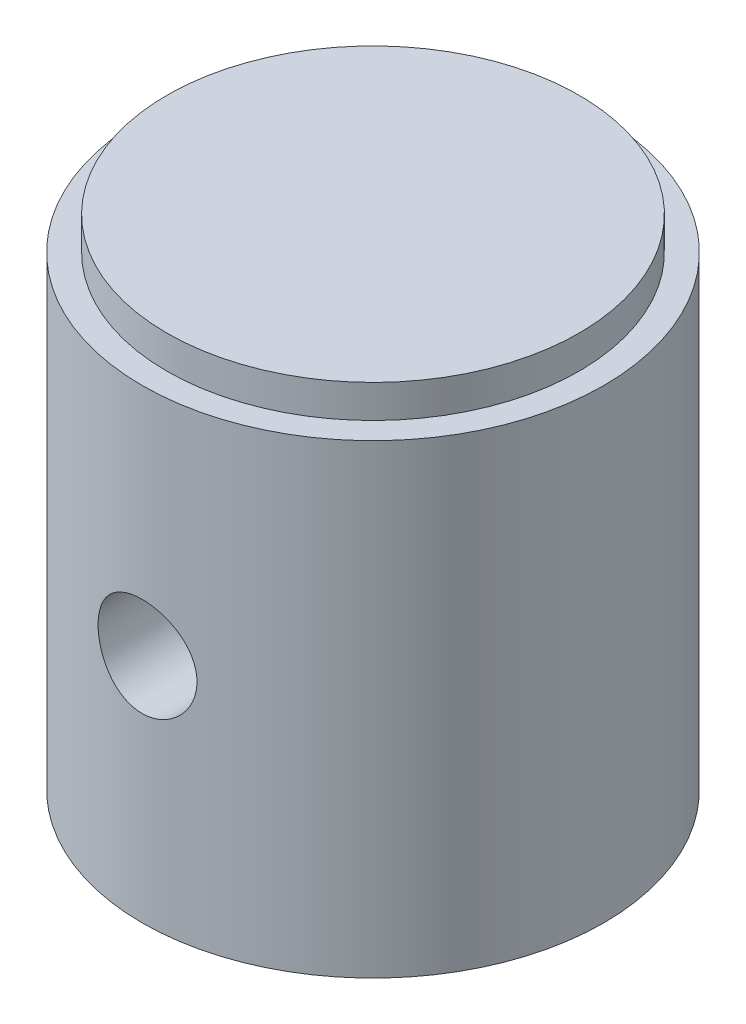
SolidWorks part; units mm, degrees
ref_plane "Front Plane" through (0, 0, 0) normal (0, 0, 1) x (1, 0, 0)
ref_plane "Top Plane" through (0, 0, 0) normal (0, 1, 0) x (1, 0, 0)
ref_plane "Right Plane" through (0, 0, 0) normal (1, 0, 0) x (0, 0, -1)
sketch "Sketch1" plane through (0, 0, 0) normal (0, 0, 1) x (1, 0, 0)
  line L0 (0, -49.5119) -> (0, 49.5119) construction
  line L1 (0, 27.1024) -> (-6.25, 27.1024)
  line L2 (-6.25, 27.1024) -> (-6.25, 26.1024)
  line L3 (-6.25, 26.1024) -> (-7, 26.1024)
  line L4 (-7, 26.1024) -> (-7, 11.9867)
  line L5 (-5.1038, 11.9867) -> (-7, 11.9867)
  line L6 (0, 27.1024) -> (0, 25.6024)
  line L7 (0, 25.6024) -> (-4.3916, 22.9636)
  line L8 (-4.3916, 22.9636) -> (-4.3916, 15.9636)
  line L9 (-5.1038, 11.9867) -> (0, 11.9867)
  line L12 (-4.3916, 18.9636) -> (-4.3916, 15.9636)
  line L13 (-4.3916, 15.9636) -> (-5.1121, 13.9843)
  line L14 (-5.1121, 13.9843) -> (-5.8391, 11.9867)
  line L15 (-4.3916, 22.9636) -> (-4.3916, 18.9636)
  point P3 (-22.7947, 20.4643)
  point P4 (0, 0)
  dimension "D4" = 1.5
  dimension "D1" = 6.25
  dimension "D2" = 1
  dimension "D3" = 0.75
  dimension "D5" = 11
  dimension "D6" = 59
  dimension "D8" = 20
revolve "Revolve1" add sketch "Sketch1" angle 360 about L0
sketch "Sketch2" plane through (0, 0, 0) normal (0, 0, 1) x (1, 0, 0)
  circle A0 centre (0, 18.9867) radius 1.5
  dimension "D2" = 3
extrude "Cut-Extrude2" cut sketch "Sketch2" against normal mid plane 14
